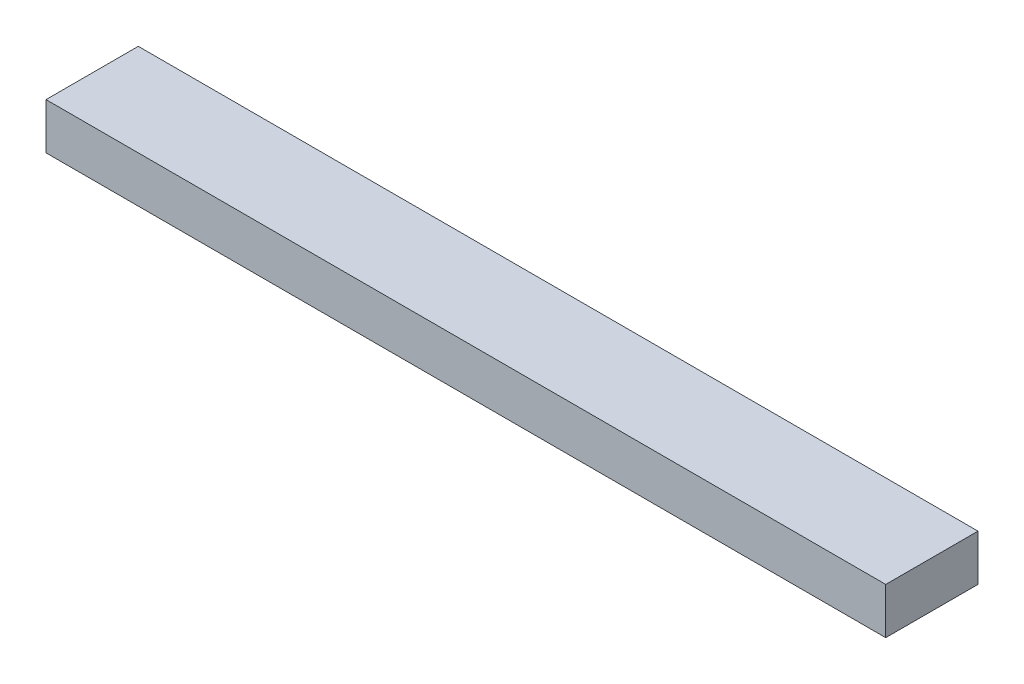
SolidWorks part; units mm, degrees
ref_plane "Front Plane" through (0, 0, 0) normal (0, 0, 1) x (1, 0, 0)
ref_plane "Top Plane" through (0, 0, 0) normal (0, 1, 0) x (1, 0, 0)
ref_plane "Right Plane" through (0, 0, 0) normal (1, 0, 0) x (0, 0, -1)
sketch "Sketch1" plane through (0, 0, 0) normal (0, 1, 0) x (1, 0, 0)
  line L1 (-57.785, -6.35) -> (57.785, -6.35)
  line L2 (-57.785, -6.35) -> (-57.785, 6.35)
  line L3 (-57.785, 6.35) -> (57.785, 6.35)
  line L4 (57.785, -6.35) -> (57.785, 6.35)
  line L5 (-57.785, -6.35) -> (57.785, 6.35) construction
  line L6 (-57.785, 6.35) -> (57.785, -6.35) construction
  point P0 (0, 0)
  dimension "D1" = 115.57
  dimension "D2" = 12.7
extrude "Boss-Extrude1" add sketch "Sketch1" along normal blind 6.35
